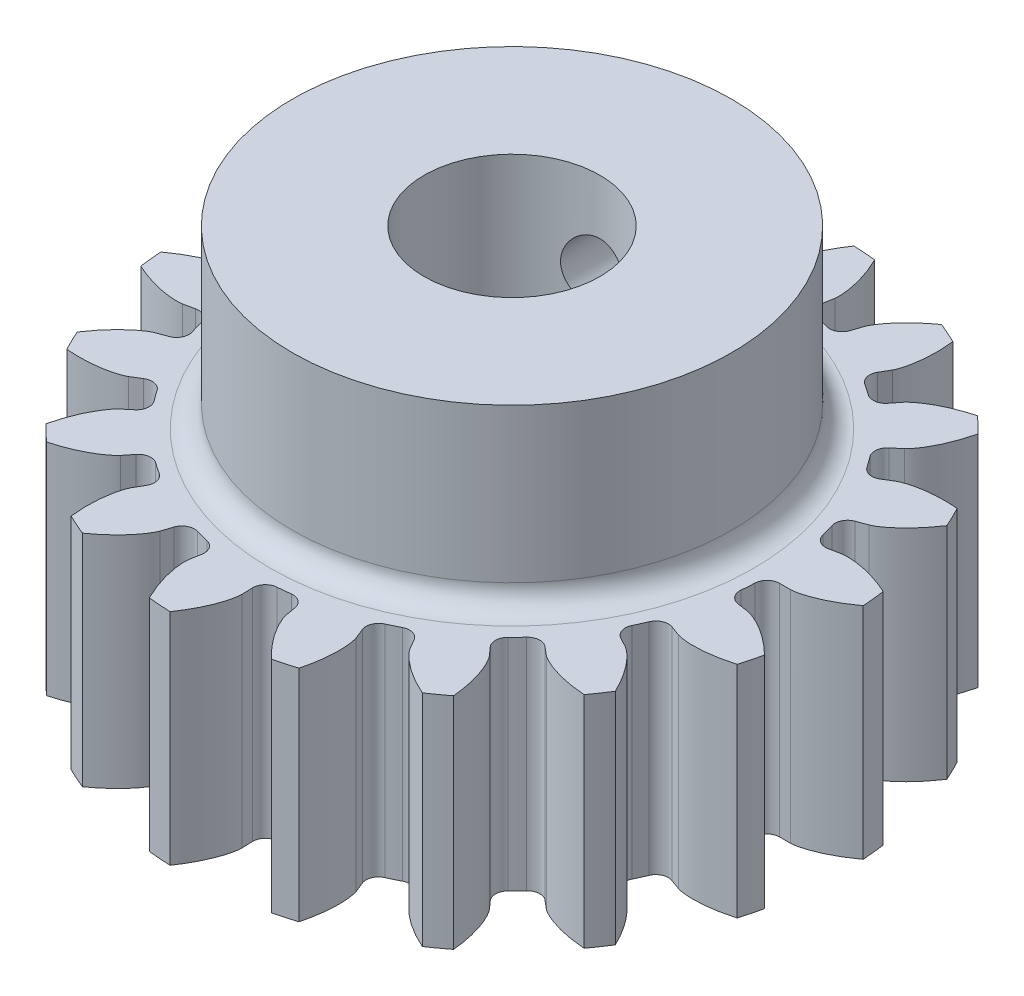
SolidWorks part; units mm, degrees
material "ABS"
ref_plane "Plan de face" through (0, 0, 0) normal (0, 0, 1) x (1, 0, 0)
ref_plane "Plan de dessus" through (0, 0, 0) normal (0, 1, 0) x (1, 0, 0)
ref_plane "Plan de droite" through (0, 0, 0) normal (1, 0, 0) x (0, 0, -1)
sketch "Esquisse1" plane through (0, 0, 0) normal (0, 1, 0) x (1, 0, 0)
  circle A0 centre (0, 0) radius 15
  circle A1 centre (0, 0) radius 11.625 construction
  circle A2 centre (0, 0) radius 13.5 construction
  circle A6 centre (0, 0) radius 12.6859 construction
  dimension "D1" = 27
  dimension "D5" = 1.5
  dimension "D6" = 1.875
  dimension "D7" = 25.3717
  dimension "D11" = 30
extrude "Boss.-Extru.1" add sketch "Esquisse1" along normal blind 10
sketch "Esquisse3" plane through (0, 0, 0) normal (0, 1, 0) x (1, 0, 0)
  spline S2 degree 4 poles (12.6859, 0) (12.6952, 0.0002) (12.7215, 0.0014) (12.7711, 0.006) (12.8517, 0.017) (12.9537, 0.036) (13.0846, 0.0664) (13.2374, 0.1094) (13.4034, 0.1643) (13.5818, 0.2322) (13.7575, 0.3069) (13.9305, 0.388) (14.1005, 0.4746) (14.3038, 0.5863) (14.5434, 0.7296) (14.8169, 0.9104) (15.1191, 1.1309) (15.4176, 1.3716) (15.7034, 1.6215) (15.9822, 1.8883) (16.2448, 2.1567) (16.5067, 2.4493) (16.7429, 2.7266) (16.9946, 3.0518) (17.1941, 3.3187) (17.4429, 3.6856) (17.5855, 3.9066) (17.7472, 4.1702) (17.8163, 4.2898) (17.859, 4.3634) knots 0 0 0 0 0 0.005377 0.015084 0.028532 0.04661 0.064855 0.092111 0.119476 0.146842 0.174209 0.201575 0.228941 0.256307 0.307035 0.361767 0.4165 0.471232 0.525964 0.580697 0.635429 0.690161 0.744894 0.799626 0.854358 0.909091 0.954545 1 1 1 1 1 construction
  spline S3 degree 4 poles (12.6859, 0) (12.6952, 0.0002) (12.7215, 0.0014) (12.7711, 0.006) (12.8517, 0.017) (12.9537, 0.036) (13.0846, 0.0664) (13.2374, 0.1094) (13.4034, 0.1643) (13.5818, 0.2322) (13.7575, 0.3069) (13.9305, 0.388) (14.1005, 0.4746) (14.3038, 0.5863) (14.5434, 0.7296) (14.8169, 0.9104) (15.1191, 1.1309) (15.4176, 1.3716) (15.7034, 1.6215) (15.9822, 1.8883) (16.2448, 2.1567) (16.5067, 2.4493) (16.7429, 2.7266) (16.9946, 3.0518) (17.1941, 3.3187) (17.3889, 3.606) (17.4821, 3.7475) (17.529, 3.8206) knots 0 0 0 0 0 0.005377 0.015084 0.028532 0.04661 0.064855 0.092111 0.119476 0.146842 0.174209 0.201575 0.228941 0.256307 0.307035 0.361767 0.4165 0.471232 0.525964 0.580697 0.635429 0.690161 0.744894 0.799626 0.854358 0.909091 0.909091 0.909091 0.909091 0.909091
sketch "Esquisse5" plane through (0, 0, 0) normal (0, 1, 0) x (1, 0, 0)
  line L0 (0, 0) -> (13.4647, -0.976) construction
  line L1 (12.6859, 0) -> (11.625, 0)
  line L2 (12.5532, -1.8295) -> (11.5035, -1.6766)
  circle A0 centre (0, 0) radius 11.625 construction
  arc A1 (11.5035, -1.6766) -> (11.625, 0) centre (0, 0) ccw
  circle A2 centre (0, 0) radius 13.5 construction
  spline S1 degree 4 poles (-4.6153, 1999.7043) (9.8867, 29.0764) (10.9116, 0.4774) (11.9105, -0.1115) (12.8517, 0.017) (12.9537, 0.036) (13.0846, 0.0664) (13.2374, 0.1094) (13.4034, 0.1643) (13.5818, 0.2322) (13.7575, 0.3069) (13.9305, 0.388) (14.1005, 0.4746) (14.3038, 0.5863) (14.5434, 0.7296) (14.8169, 0.9104) (15.1191, 1.1309) (15.4176, 1.3716) (15.7034, 1.6215) (15.9822, 1.8883) (16.2448, 2.1567) (16.5067, 2.4493) (16.7429, 2.7266) (16.9946, 3.0518) (17.9626, 4.3469) (20.585, 8.859) (-12.9238, -42.5101) (1097.0378, 1687.289) knots -0.497849 -0.497849 -0.497849 -0.497849 -0.497849 0.005377 0.015084 0.028532 0.04661 0.064855 0.092111 0.119476 0.146842 0.174209 0.201575 0.228941 0.256307 0.307035 0.361767 0.4165 0.471232 0.525964 0.580697 0.635429 0.690161 0.744894 0.799626 0.854358 1.752643 1.752643 1.752643 1.752643 1.752643 only from (12.6859, 0) to (17.529, 3.8206) construction
  spline S2 degree 4 poles (12.6859, 0) (12.6952, 0.0002) (12.7215, 0.0014) (12.7711, 0.006) (12.8517, 0.017) (12.9537, 0.036) (13.0846, 0.0664) (13.2374, 0.1094) (13.4034, 0.1643) (13.5818, 0.2322) (13.7575, 0.3069) (13.9305, 0.388) (14.1005, 0.4746) (14.3038, 0.5863) (14.5434, 0.7296) (14.8169, 0.9104) (15.1191, 1.1309) (15.4176, 1.3716) (15.7034, 1.6215) (15.9822, 1.8883) (16.2448, 2.1567) (16.5067, 2.4493) (16.7429, 2.7266) (16.9946, 3.0518) (17.1941, 3.3187) (17.3889, 3.606) (17.4821, 3.7475) (17.529, 3.8206) knots 0 0 0 0 0 0.005377 0.015084 0.028532 0.04661 0.064855 0.092111 0.119476 0.146842 0.174209 0.201575 0.228941 0.256307 0.307035 0.361767 0.4165 0.471232 0.525964 0.580697 0.635429 0.690161 0.744894 0.799626 0.854358 0.909091 0.909091 0.909091 0.909091 0.909091
  spline S3 degree 4 poles (12.5532, -1.8295) (12.5625, -1.8311) (12.5883, -1.836) (12.6367, -1.8478) (12.7149, -1.8703) (12.8131, -1.9038) (12.9383, -1.9527) (13.0832, -2.0174) (13.2396, -2.0956) (13.4063, -2.1885) (13.5694, -2.2878) (13.7289, -2.393) (13.8847, -2.5033) (14.0697, -2.6431) (14.2861, -2.8194) (14.5307, -3.0378) (14.7979, -3.2995) (15.0586, -3.5808) (15.3053, -3.8693) (15.5428, -4.1735) (15.764, -4.4769) (15.9809, -4.8043) (16.1746, -5.1127) (16.3768, -5.4709) (16.5357, -5.7637) (16.6871, -6.0761) (16.7588, -6.2296) (16.7947, -6.3087) knots 0 0 0 0 0 0.005377 0.015084 0.028532 0.04661 0.064855 0.092111 0.119476 0.146842 0.174209 0.201575 0.228941 0.256307 0.307035 0.361767 0.4165 0.471232 0.525964 0.580697 0.635429 0.690161 0.744894 0.799626 0.854358 0.909091 0.909091 0.909091 0.909091 0.909091
  point P6 (13.4985, 0.2012)
  dimension "D1" = 5
extrude "Enlèv. mat.-Extru.1" cut sketch "Esquisse5" against normal through all and the other way through all
fillet "Congé1" radius 0.57 2 edges at (11.5035, 5, 1.6766) (11.625, 5, 0)
pattern_circular "Répétition circulaire1" count 18 over 360 about axis through (0, 10, 0) along (0, 1, 0) of "Enlèv. mat.-Extru.1", "Congé1"
sketch "Esquisse6" plane through (0, 10, 0) normal (0, 1, 0) x (1, 0, 0)
  circle A0 centre (0, 0) radius 4
  dimension "D1" = 8
extrude "Enlèv. mat.-Extru.2" cut sketch "Esquisse6" against normal through all
sketch "Esquisse7" plane through (0, 10, 0) normal (0, 1, 0) x (1, 0, 0)
  circle A0 centre (0, 0) radius 4 construction
  circle A1 centre (0, 0) radius 10
  circle A2 centre (0, 0) radius 4
  dimension "D1" = 20
extrude "Boss.-Extru.2" add sketch "Esquisse7" along normal blind 8
fillet "Congé2" radius 1 1 edges at (0, 10, 10)
sketch "Esquisse8" plane through (0, 0, 0) normal (0, 0, 1) x (1, 0, 0)
  line L0 (10, 18) -> (-10, 18) construction
  circle A0 centre (0, 14) radius 1.5
  dimension "D1" = 4
  dimension "D2" = 3
extrude "Enlèv. mat.-Extru.3" cut sketch "Esquisse8" against normal through all
equation "\"D1@Esquisse1\"= \"Module\" * \"Z1\""
equation "\"Module\"= 1.5'module"
equation "\"Z1\"= 18'nb de dents"
equation "\"D5@Esquisse1\"=\"Module\""
equation "\"D6@Esquisse1\"=\"Module\"*1.25"
equation "\"a\"= 20'angle pression"
equation "\"D7@Esquisse1\"=\"D1@Esquisse1\"*cos( \"a\")"
equation "\"rayon\"= \"Module\" * 0.38'R fond de dent"
equation "\"D1@Esquisse5\"=360/\"Z1\"/4"
equation "\"D1@Répétition circulaire1\"=\"Z1\""
equation "\"D1@Congé1\"=\"rayon\""
